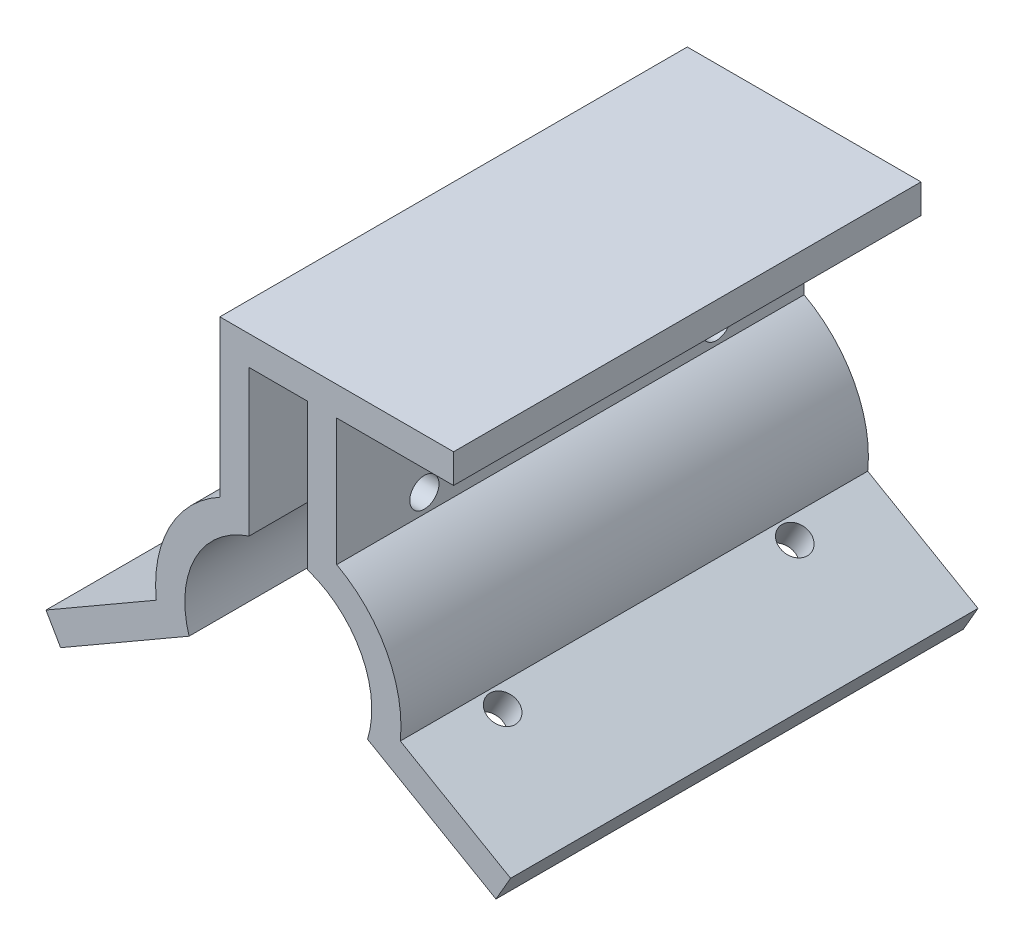
SolidWorks part; units mm, degrees
material "Custom Plastic"
ref_plane "Front Plane" through (0, 0, 0) normal (0, 0, 1) x (1, 0, 0)
ref_plane "Top Plane" through (0, 0, 0) normal (0, 1, 0) x (1, 0, 0)
ref_plane "Right Plane" through (0, 0, 0) normal (1, 0, 0) x (0, 0, -1)
sketch "Sketch1" plane through (0, 0, 0) normal (0, 0, 1) x (1, 0, 0)
  line L0 (13.8564, -8) -> (35.507, -20.5) construction
  line L1 (-13.8564, -8) -> (-35.507, -20.5) construction
  line L2 (0, 40.1987) -> (0, -40.1987) construction
  line L3 (-58.9085, 0) -> (58.9085, 0) construction
  line L4 (-20.1635, -5.8679) -> (-38.007, -16.1699) construction
  line L5 (20.1635, -5.8679) -> (38.007, -16.1699) construction
  line L6 (-2.5, 4.3301) -> (-38.007, -16.1699) construction
  line L7 (2.5, 4.3301) -> (38.007, -16.1699) construction
  line L8 (0, 0) -> (35.507, -20.5) construction
  line L9 (0, 0) -> (-35.507, -20.5) construction
  line L10 (35.507, -20.5) -> (38.007, -16.1699) construction
  line L11 (-38.007, -16.1699) -> (-35.507, -20.5) construction
  line L12 (-5, 40.1987) -> (-5, 15.1987)
  line L13 (5, 40.1987) -> (5, 15.1987)
  line L14 (-10, 40.1987) -> (-10, 18.4662)
  line L15 (10, 40.1987) -> (10, 18.4662)
  line L16 (-5, 40.1987) -> (5, 40.1987)
  line L17 (10, 40.1987) -> (10, -40.1987) construction
  line L19 (5, 40.1987) -> (5, -40.1987) construction
  line L20 (10, 45.1987) -> (-10, 45.1987)
  line L21 (-10, 40.1987) -> (-10, -40.1987) construction
  line L22 (-10, 45.1987) -> (-10, 40.1987)
  line L23 (-5, 40.1987) -> (-5, -40.1987) construction
  line L24 (10, 45.1987) -> (30, 45.1987)
  line L25 (30, 45.1987) -> (30, 40.1987)
  line L26 (30, 40.1987) -> (10, 40.1987)
  line L27 (15.2708, -4.7752) -> (37.257, -17.4689)
  line L28 (15.9894, 0.5835) -> (39.757, -13.1388)
  line L29 (21.9135, -2.8368) -> (39.757, -13.1388) construction
  line L30 (39.757, -13.1388) -> (37.257, -17.4689)
  line L31 (15.6064, -4.9689) -> (37.257, -17.4689) construction
  line L32 (-15.2708, -4.7752) -> (-37.257, -17.4689)
  line L33 (-15.9894, 0.5835) -> (-39.757, -13.1388)
  line L34 (-21.9135, -2.8368) -> (-39.757, -13.1388) construction
  line L35 (-15.6064, -4.9689) -> (-37.257, -17.4689) construction
  line L36 (-39.757, -13.1388) -> (-37.257, -17.4689)
  line L41 (-7.62, -8.6709) -> (-26.4696, -20.0152) construction
  line L42 (-7.62, -8.6709) -> (-11.2296, -2.6733) construction
  line L43 (-26.4696, -20.0152) -> (-30.0792, -14.0176) construction
  line L44 (-11.2296, -2.6733) -> (-30.0792, -14.0176) construction
  line L45 (-20.8608, -8.0025) -> (-17.0448, -14.3431) construction
  circle A0 centre (0, 0) radius 11 construction
  arc A1 (13.8564, -8) -> (5, 15.1987) centre (0, 0) ccw
  arc A2 (20.1635, -5.8679) -> (10, 18.4662) centre (0, 0) ccw
  circle A3 centre (0, 0) radius 21 construction
  circle A4 centre (0, 0) radius 16 construction
  arc A5 (-10, 18.4662) -> (-20.1635, -5.8679) centre (0, 0) ccw
  arc A6 (-5, 15.1987) -> (-13.8564, -8) centre (0, 0) ccw
  point P11 (0, 0)
  point P14 (0, 0)
  point P21 (18.1865, -10.5)
  point P52 (13.553, -6.9982)
  point P60 (-9.4248, -5.6721)
  dimension "D1" = 22
  dimension "D2" = 5
  dimension "D4" = 30
  dimension "D5" = 30
  dimension "D8" = 20
  dimension "D14" = 5
  dimension "D13" = 25
  dimension "D15" = 20
  dimension "D20" = 22
  dimension "D21" = 7
  dimension "D22" = 0.6
  dimension "D3" = 5
  dimension "D6" = 5
  dimension "D7" = 5
  dimension "D9" = 5
  dimension "D10" = 5
  dimension "D11" = 5
  dimension "D12" = 5
  dimension "D16" = 3.5
  dimension "D17" = 3.5
  dimension "D18" = 3.5
  dimension "D19" = 3.5
extrude "Boss-Extrude1" add sketch "Sketch1" along normal blind 80
hole_wizard "Ø5.0mm Dowel Hole1" positions "Sketch2" profile "Sketch3" hole size "Ø5.0" standard "ANSI Metric"
sketch "Sketch2" plane through (1.75, 3.0311, 0) normal (-0.5, -0.866, 0) x (-0.866, 0.5, 0)
  line L0 (-15.6125, -80) -> (-15.6125, 0) construction
  line L1 (-15.6125, -80) -> (-41, -80) construction
  line L2 (-15.6125, 0) -> (-41, 0) construction
  point P0 (-22.1125, -65)
  point P2 (-22.1125, -15)
  dimension "D1" = 6.5
  dimension "D2" = 15
  dimension "D3" = 15
sketch "Sketch3" plane through (20.9, -8.0252, 65) normal (0, 0, 1) x (0.866, -0.5, 0)
  line L0 (0, 0) -> (0, 11.5022)
  line L1 (0, 11.5022) -> (2.5, 10)
  line L2 (2.5, 10) -> (2.5, 0)
  line L5 (2.5, 0) -> (0, 0)
  line L10 (0, 11.5022) -> (-2.5, 10) construction
  line L11 (0, -6.35) -> (0, 107.95) construction
  dimension "Hole Dia." = 5
  dimension "Hole Depth" = 10
  dimension "Drill Angle" = 118
mirror "Mirror1" about plane through (0, 0, 0) normal (1, 0, 0) of "Ø5.0mm Dowel Hole1"
hole_wizard "Ø5.0mm Dowel Hole2" positions "Sketch4" profile "Sketch5" hole size "Ø5.0" standard "ANSI Metric"
sketch "Sketch4" plane through (-5, 0, 0) normal (1, 0, 0) x (0, 0, -1)
  line L0 (0, 40.1987) -> (0, 15.1987) construction
  line L1 (-80, 40.1987) -> (-80, 15.1987) construction
  line L2 (-80, 15.1987) -> (0, 15.1987) construction
  point P0 (-15, 21.6987)
  point P2 (-65, 21.6987)
  dimension "D1" = 15
  dimension "D2" = 15
  dimension "D3" = 6.5
sketch "Sketch5" plane through (-5, 21.6987, 15) normal (0, 1, 0) x (0, 0, -1)
  line L0 (0, 0) -> (0, 34.757)
  line L1 (0, 34.757) -> (2.5, 34.757)
  line L2 (2.5, 34.757) -> (2.5, 0)
  line L5 (2.5, 0) -> (0, 0)
  line L11 (0, -6.35) -> (0, 107.95) construction
  dimension "Thru Hole Dia." = 5
  dimension "Thru Hole Depth" = 34.757
mirror "Mirror2" about plane through (0, 0, 0) normal (1, 0, 0) of "Ø5.0mm Dowel Hole2"
equation "\"pipe_od\"=22"
equation "\"D1@Sketch1\"=\"pipe_od\""
